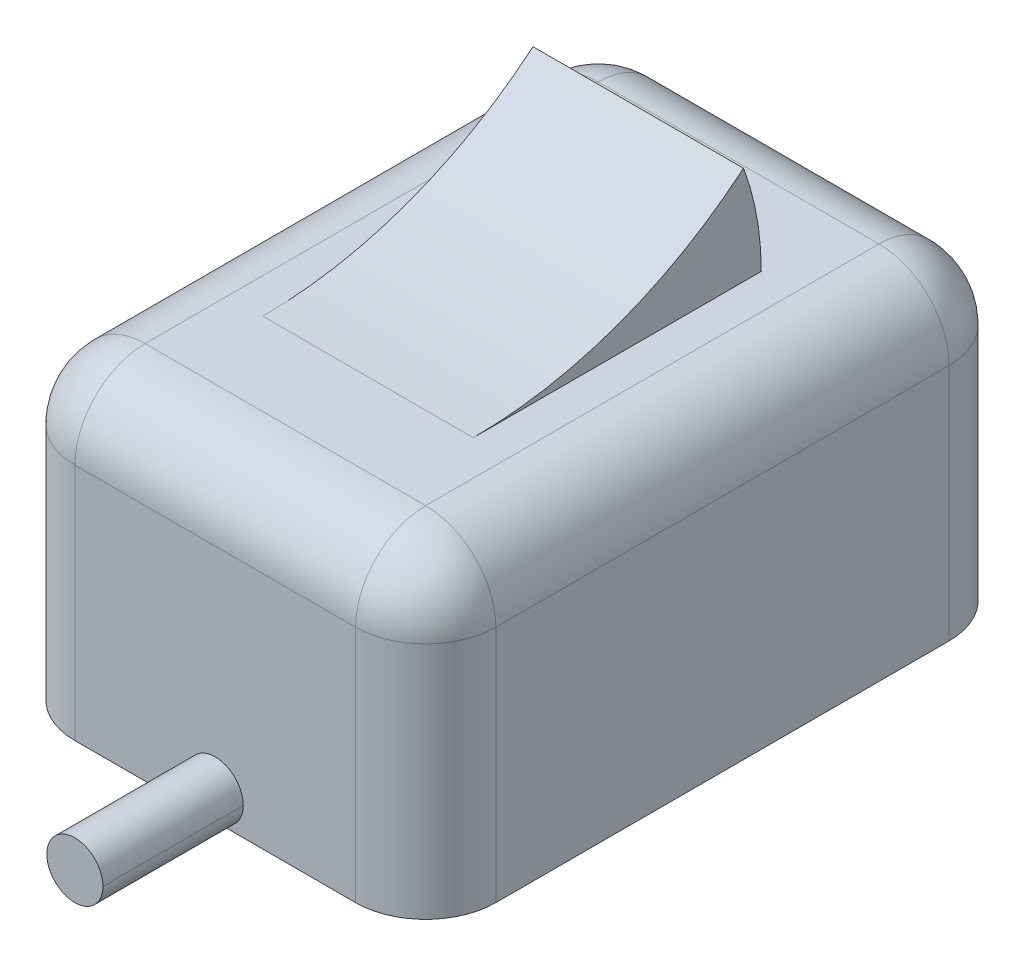
SolidWorks part; units mm, degrees
ref_plane "Front Plane" through (0, 0, 0) normal (0, 0, 1) x (1, 0, 0)
ref_plane "Top Plane" through (0, 0, 0) normal (0, 1, 0) x (1, 0, 0)
ref_plane "Right Plane" through (0, 0, 0) normal (1, 0, 0) x (0, 0, -1)
sketch "Sketch1" plane through (0, 0, 0) normal (0, 1, 0) x (1, 0, 0)
  line L1 (0, 0) -> (30, 0)
  line L2 (0, 0) -> (0, 42.3)
  line L3 (0, 42.3) -> (30, 42.3)
  line L4 (30, 0) -> (30, 42.3)
  dimension "D1" = 42.3
  dimension "D2" = 30
extrude "Boss-Extrude1" add sketch "Sketch1" along normal blind 22
sketch "Sketch2" plane through (0, 0, 0) normal (0, 0, 1) x (1, 0, 0)
  line L1 (0, 0) -> (30, 0) construction
  circle A0 centre (15, 2) radius 2
  point P6 (15, 0)
  dimension "D1" = 4
extrude "Boss-Extrude2" add sketch "Sketch2" along normal blind 10
fillet "Fillet2" radius 5 8 edges at (30, 11, -42.3) (30, 22, -21.15) (15, 22, 0) (30, 11, 0) (0, 11, 0) (0, 11, -42.3) (0, 22, -21.15) (15, 22, -42.3)
sketch "Sketch5" plane through (0, 0, 0) normal (1, 0, 0) x (0, 0, -1)
  line L0 (10.8868, 22) -> (31.4132, 22)
  line L1 (5, 22) -> (37.3, 22) construction
  line L2 (31.4132, 22) -> (31.4132, 31.3662) construction
  arc A0 (10.8868, 22) -> (30.1482, 29) centre (10.8868, 52) ccw
  arc A1 (31.4132, 22) -> (30.1482, 29) centre (11.4132, 22) ccw
  point P2 (21.15, 22)
  point P5 (21.15, 22)
  dimension "D1" = 20
  dimension "D2" = 30
  dimension "D3" = 7
extrude "Boss-Extrude4" add sketch "Sketch5" along normal blind 30
sketch "Sketch6" plane through (0, 0, 0) normal (-1, 0, 0) x (0, 0, 1)
  line L0 (-10.8868, 22) -> (-31.4132, 22) construction
  line L1 (-10.8868, 22) -> (-31.4132, 22)
  arc A0 (-30.1482, 29) -> (-31.4132, 22) centre (-11.4132, 22) ccw construction
  arc A1 (-30.1482, 29) -> (-10.8868, 22) centre (-10.8868, 52) ccw construction
  arc A2 (-30.1482, 29) -> (-31.4132, 22) centre (-11.4132, 22) ccw
  arc A3 (-30.1482, 29) -> (-10.8868, 22) centre (-10.8868, 52) ccw
extrude "Cut-Extrude1" cut sketch "Sketch6" against normal blind 7.5
sketch "Sketch7" plane through (30, 0, 0) normal (1, 0, 0) x (0, 0, -1)
  line L0 (10.8868, 22) -> (31.4132, 22) construction
  line L1 (10.8868, 22) -> (31.4132, 22)
  arc A0 (31.4132, 22) -> (30.1482, 29) centre (11.4132, 22) ccw construction
  arc A1 (10.8868, 22) -> (30.1482, 29) centre (10.8868, 52) ccw construction
  arc A2 (31.4132, 22) -> (30.1482, 29) centre (11.4132, 22) ccw
  arc A3 (10.8868, 22) -> (30.1482, 29) centre (10.8868, 52) ccw
extrude "Cut-Extrude2" cut sketch "Sketch7" against normal blind 7.5
split line "Split Line1"
sketch "Sketch8" plane through (0, 0, 0) normal (0, 1, 0) x (1, 0, 0)
  line L5 (25, 42.3) -> (5, 42.3)
  line L6 (30, 5) -> (30, 37.3)
  line L7 (15, 0) -> (25, 0)
  line L8 (5, 0) -> (15, 0)
  line L9 (0, 37.3) -> (0, 5)
  line L10 (25, 42.3) -> (5, 42.3)
  line L11 (30, 5) -> (30, 37.3)
  line L12 (15, 0) -> (25, 0)
  line L13 (5, 0) -> (15, 0)
  line L14 (0, 37.3) -> (0, 5)
  arc A4 (30, 37.3) -> (25, 42.3) centre (25, 37.3) ccw
  arc A5 (25, 0) -> (30, 5) centre (25, 5) ccw
  arc A6 (0, 5) -> (5, 0) centre (5, 5) ccw
  arc A7 (5, 42.3) -> (0, 37.3) centre (5, 37.3) ccw
  arc A8 (30, 37.3) -> (25, 42.3) centre (25, 37.3) ccw
  arc A9 (25, 0) -> (30, 5) centre (25, 5) ccw
  arc A10 (0, 5) -> (5, 0) centre (5, 5) ccw
  arc A11 (5, 42.3) -> (0, 37.3) centre (5, 37.3) ccw
  dimension "D1" = 0
